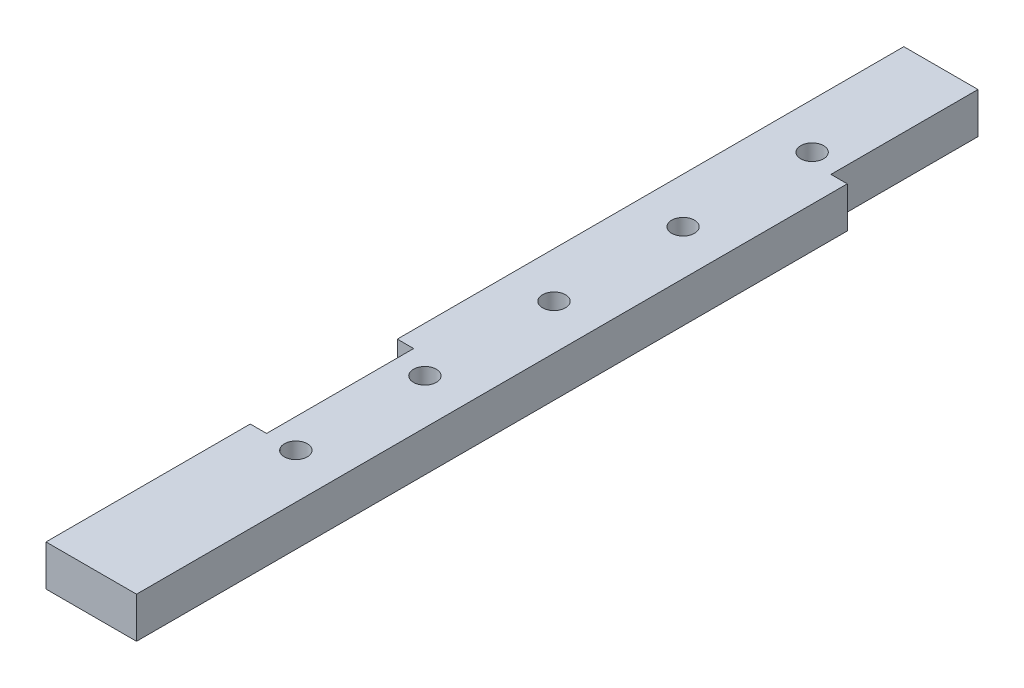
SolidWorks part; units mm, degrees
ref_plane "Front Plane" through (0, 0, 0) normal (0, 0, 1) x (1, 0, 0)
ref_plane "Top Plane" through (0, 0, 0) normal (0, 1, 0) x (1, 0, 0)
ref_plane "Right Plane" through (0, 0, 0) normal (1, 0, 0) x (0, 0, -1)
sketch "Sketch1" plane through (0, 0, 0) normal (0, 0, 1) x (1, 0, 0)
  line L1 (0, 0) -> (69.85, 0)
  line L2 (0, 0) -> (0, 6.35)
  line L3 (0, 6.35) -> (69.85, 6.35)
  line L4 (69.85, 0) -> (69.85, 6.35)
  dimension "D1" = 6.35
  dimension "D2" = 69.85
extrude "Boss-Extrude1" add sketch "Sketch1" along normal blind 120.65
sketch "Sketch2" plane through (0, 6.35, 0) normal (0, 1, 0) x (1, 0, 0)
  line L0 (35.9237, 0) -> (35.9237, -37.803)
  line L1 (69.85, 0) -> (35.9237, 0)
  line L2 (69.85, 0) -> (69.85, -55.9623)
  line L4 (35.9237, -37.803) -> (69.85, -55.9623)
extrude "Cut-Extrude1" cut sketch "Sketch2" against normal through all
sketch "Sketch3" plane through (0, 0, 0) normal (0, -1, 0) x (1, 0, 0)
  line L0 (0, 0) -> (35.9237, 0) construction
  line L1 (19.1516, 0) -> (5.08, 0)
  line L2 (19.1516, 0) -> (19.1516, 120.65)
  line L3 (19.1516, 120.65) -> (5.08, 120.65)
  line L4 (5.08, 0) -> (5.08, 120.65)
  line L5 (0, 120.65) -> (69.85, 120.65) construction
  line L7 (5.08, 120.65) -> (0, 120.65)
  line L9 (5.08, 0) -> (0, 0)
  line L10 (0, 120.65) -> (0, 0)
  line L11 (19.1516, 0) -> (69.85, 0)
  line L13 (19.1516, 120.65) -> (69.85, 120.65)
  line L14 (69.85, 0) -> (69.85, 120.65)
  line M1 (35.9237, 0) -> (35.9237, 37.803)
  line M2 (35.9237, 37.803) -> (69.85, 55.9623)
  line M3 (69.85, 55.9623) -> (69.85, 120.65)
  line M4 (69.85, 120.65) -> (0, 120.65)
  line M5 (0, 120.65) -> (0, 0)
  line M6 (0, 0) -> (35.9237, 0)
  dimension "D1" = 5.08
  dimension "D2" = 14.0716
extrude "Cut-Extrude2" cut sketch "Sketch3" against normal blind 42.164 contours L2 M6 M1 M2 M3 M4 | L4 M6 M4 M5
sketch "Sketch4" plane through (0, 0, 0) normal (0, -1, 0) x (1, 0, 0)
  line L0 (5.08, 0) -> (5.08, 120.65) construction
  line L1 (5.08, 88.9) -> (7.62, 88.9)
  line L2 (5.08, 88.9) -> (5.08, 66.04)
  line L3 (5.08, 66.04) -> (7.62, 66.04)
  line L4 (7.62, 88.9) -> (7.62, 66.04)
  line L5 (19.1516, 0) -> (19.1516, 120.65) construction
  line L6 (19.1516, -12.7) -> (16.6116, -12.7)
  line L7 (19.1516, -12.7) -> (19.1516, 10.16)
  line L8 (19.1516, 10.16) -> (16.6116, 10.16)
  line L9 (16.6116, -12.7) -> (16.6116, 10.16)
  line L10 (5.08, 120.65) -> (19.1516, 120.65) construction
  point P12 (12.1158, 120.65)
  dimension "D1" = 2.54
  dimension "D2" = 22.86
  dimension "D3" = 31.75
  dimension "D4" = 55.88
  dimension "D5" = 2.54
  dimension "D6" = 22.86
extrude "Cut-Extrude3" cut sketch "Sketch4" against normal up to surface (6.35 mm away) up to face at (12.1158, 6.35, 60.325)
sketch "Sketch5" plane through (0, 0, 0) normal (0, -1, 0) x (1, 0, 0)
  line L1 (5.08, 0) -> (16.6116, 0)
  line L2 (5.08, 0) -> (5.08, -12.7)
  line L3 (5.08, -12.7) -> (16.6116, -12.7)
  line L4 (16.6116, -12.7) -> (19.1516, -12.7)
  line L5 (16.6116, 10.16) -> (16.6116, -12.7)
  line L6 (19.1516, 10.16) -> (16.6116, 10.16)
  line L7 (19.1516, -12.7) -> (19.1516, 10.16)
  line L8 (16.6116, -12.7) -> (19.1516, -12.7)
  line L9 (16.6116, 10.16) -> (16.6116, -12.7)
  line L10 (19.1516, 10.16) -> (16.6116, 10.16)
  line L11 (19.1516, -12.7) -> (19.1516, 10.16)
  line L12 (7.62, 88.9) -> (5.08, 88.9)
  line L13 (7.62, 66.04) -> (7.62, 88.9)
  line L14 (5.08, 66.04) -> (7.62, 66.04)
  line L15 (5.08, 88.9) -> (5.08, 66.04)
  line L16 (7.62, 88.9) -> (5.08, 88.9)
  line L17 (7.62, 66.04) -> (7.62, 88.9)
  line L18 (5.08, 66.04) -> (7.62, 66.04)
  line L19 (5.08, 88.9) -> (5.08, 66.04)
  line L20 (16.6116, 0) -> (16.6116, -12.7)
  line M9 (5.08, 0) -> (16.6116, 0)
  dimension "D1" = 0
  dimension "D2" = 0
extrude "Boss-Extrude2" add sketch "Sketch5" against normal up to surface (6.35 mm away) contours L9 L2 L3 M9 up to face at (10.7086, 6.35, 57.15)
sketch "Sketch6" plane through (0, 0, 0) normal (0, -1, 0) x (1, 0, 0)
  line L0 (5.08, 120.65) -> (19.1516, 120.65) construction
  line L1 (19.1516, 10.16) -> (19.1516, 120.65) construction
  circle A0 centre (12.1666, 88.9) radius 1.778
  circle A1 centre (12.1666, 68.834) radius 1.778
  circle A2 centre (0, 0) radius 1.778
  circle A3 centre (12.1666, 48.768) radius 1.778
  circle A4 centre (12.1666, 28.702) radius 1.778
  circle A5 centre (12.1666, 8.636) radius 1.778
  dimension "D1" = 3.556
  dimension "D5" = 3.556
  dimension "D2" = 31.75
  dimension "D3" = 6.985
  dimension "D4" = 20.066
  dimension "D6" = 20.066
  dimension "D7" = 20.066
  dimension "D8" = 20.066
extrude "Cut-Extrude4" cut sketch "Sketch6" against normal up to surface (6.35 mm away) up to face at (10.7086, 6.35, 54.61)
